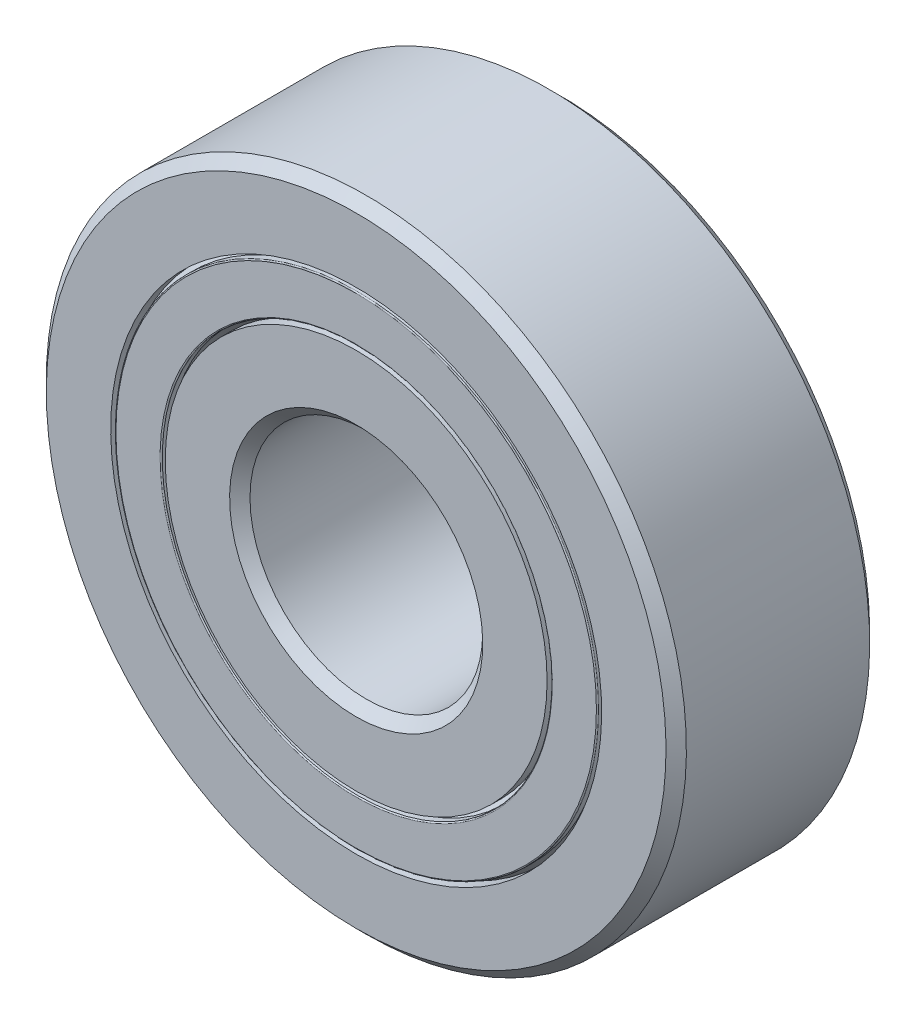
SolidWorks part; units mm, degrees
ref_plane "Front Plane" through (0, 0, 0) normal (0, 0, 1) x (1, 0, 0)
ref_plane "Top Plane" through (0, 0, 0) normal (0, 1, 0) x (1, 0, 0)
ref_plane "Right Plane" through (0, 0, 0) normal (1, 0, 0) x (0, 0, -1)
sketch "Sketch1" plane through (0, 0, 0) normal (0, 0, 1) x (1, 0, 0)
  line L0 (-11, 0) -> (11, 0) construction
  line L1 (-4, 0) -> (4, 0) construction
  circle A0 centre (0, 0) radius 4 construction
  circle A1 centre (0, 0) radius 11 construction
  point P3 (0, 0)
  point P6 (0, 0)
  point P7 (0, -4)
  point P11 (0, -11)
  point P12 (0, 4)
  point P13 (0, 11)
  dimension "OD" = 22
  dimension "ID" = 8
sketch "Sketch2" plane through (0, 0, 0) normal (1, 0, 0) x (0, 0, -1)
  line L0 (-3.5, 11) -> (3.5, 11) construction
  line L1 (0, 11) -> (0, -11) construction
  line L2 (3.15, 11) -> (-3.15, 11)
  line L3 (-3.15, 11) -> (-3.5, 10.65)
  line L4 (-3.5, 10.65) -> (-3.5, 8.4375)
  line L5 (-3.5, 8.4375) -> (-1.5556, 8.4375)
  line L6 (3.5, 8.4375) -> (1.5556, 8.4375)
  line L7 (3.5, 10.65) -> (3.5, 8.4375)
  line L8 (3.15, 11) -> (3.5, 10.65)
  line L9 (0, 11) -> (0, 7.5) construction
  line L10 (0, 7.5) -> (0, 4) construction
  line L11 (0, 11) -> (0, -11) construction
  line L12 (-3.5, 0) -> (3.5, 0) construction
  line L13 (3.5, 4) -> (-3.5, 4) construction
  line L14 (0, 9.3162) -> (0, 5.6838) construction
  line L15 (-3.5, -4) -> (3.5, -4) construction
  line L16 (-3.5, 4) -> (-3.5, -4) construction
  line L17 (3.5, 11) -> (3.5, -11) construction
  line L18 (-3.5, 8.4375) -> (-3.5, 8.3438) construction
  line L19 (-3.5, 8.3438) -> (-3.5, 8.25) construction
  line L20 (-3.5, 8.25) -> (-3.5, 8.1562) construction
  line L21 (-3.5, 8.1562) -> (-3.5, 8.0625) construction
  line L22 (-3.5, 8.0625) -> (-3.5, 7.9688) construction
  line L24 (-2.5278, 8.4375) -> (-2.5278, 7.5) construction
  arc A0 (-1.5556, 8.4375) -> (1.5556, 8.4375) centre (0, 7.5) cw
  circle A1 centre (0, 7.5) radius 1.8162 construction
  point P14 (0, 4)
  point P17 (0, 0)
  point P21 (0, 11)
  point P29 (0, 4)
  point P30 (0, -4)
  point P46 (-2.5278, 7.9688)
  dimension "Width" = 7
  dimension "D1" = 45
  dimension "D2" = 0.35
  dimension "D3" = 3.1111
  dimension "D4" = 0.9375
  dimension "For Shaft Diameter" = 8
  dimension "For Housing ID" = 22
sketch "Sketch3" plane through (0, 0, 0) normal (1, 0, 0) x (0, 0, -1)
  line L0 (3.15, 11) -> (3.5, 10.65) construction
  line L1 (3.5, 10.65) -> (3.5, 8.4375) construction
  line L2 (3.5, 8.4375) -> (1.5556, 8.4375) construction
  line L3 (-3.5, 8.4375) -> (-1.5556, 8.4375) construction
  line L4 (-3.5, 10.65) -> (-3.5, 8.4375) construction
  line L5 (-3.15, 11) -> (-3.5, 10.65) construction
  line L6 (3.15, 11) -> (-3.15, 11) construction
  line L7 (3.15, 11) -> (3.5, 10.65)
  line L8 (3.5, 10.65) -> (3.5, 8.4375)
  line L9 (3.5, 8.4375) -> (1.5556, 8.4375)
  line L10 (-3.5, 8.4375) -> (-1.5556, 8.4375)
  line L11 (-3.5, 10.65) -> (-3.5, 8.4375)
  line L12 (-3.15, 11) -> (-3.5, 10.65)
  line L13 (3.15, 11) -> (-3.15, 11)
  arc A0 (1.5556, 8.4375) -> (-1.5556, 8.4375) centre (0, 7.5) ccw construction
  arc A1 (1.5556, 8.4375) -> (-1.5556, 8.4375) centre (0, 7.5) ccw
revolve "Revolve1" add sketch "Sketch3" angle 360 about L12
sketch "Sketch4" plane through (0, 0, 0) normal (1, 0, 0) x (0, 0, -1)
  line L0 (0, 11) -> (0, -11) construction
  line L1 (0, 11) -> (0, -11) construction
  line L2 (-3.15, 4) -> (-3.5, 4.35)
  line L3 (-3.5, 4.35) -> (-3.5, 6.5625)
  line L5 (-3.5, 6.5625) -> (-1.5556, 6.5625)
  line L6 (-3.15, 4) -> (3.15, 4)
  line L8 (3.15, 4) -> (3.5, 4.35)
  line L10 (3.5, 4.35) -> (3.5, 6.5625)
  line L11 (3.5, 6.5625) -> (1.5556, 6.5625)
  line L12 (-3.5, 10.65) -> (-3.5, 8.4375) construction
  line L13 (3.15, 11) -> (3.5, 10.65) construction
  line L15 (3.5, -10.65) -> (3.5, 10.65) construction
  line L16 (3.15, 11) -> (3.15, -11) construction
  arc A1 (1.5556, 6.5625) -> (-1.5556, 6.5625) centre (0, 7.5) cw
  circle A2 centre (0, 7.5) radius 1.8162 construction
  point P1 (0, 4)
revolve "Revolve2" add sketch "Sketch4" angle 360 about L12
sketch "Sketch5" plane through (0, 0, 0) normal (1, 0, 0) x (0, 0, -1)
  line L0 (-1.8162, 7.5) -> (1.8162, 7.5)
  arc A2 (-1.8162, 7.5) -> (1.8162, 7.5) centre (0, 7.5) cw
  arc A3 (1.5556, 8.4375) -> (-1.5556, 8.4375) centre (0, 7.5) ccw construction
revolve "Revolve3" add sketch "Sketch5" angle 360 about L0
sketch "Sketch6" plane through (0, 0, 0) normal (1, 0, 0) x (0, 0, -1)
  line L0 (-3.5, 8.4375) -> (-3.5, 7.9688) construction
  line L1 (-3.5, 10.65) -> (-3.5, -10.65) construction
  line L2 (-3.5, 7.9688) -> (-3.5, 7.5) construction
  line L3 (-3.5, 7.5) -> (-3.5, 7.0312) construction
  line L4 (-3.5, 7.0312) -> (-3.5, 6.5625) construction
  line L5 (-3.5, 7.9688) -> (-3.2091, 7.9688) construction
  line L7 (-1.7547, 7.9687) -> (-1.7547, 7.0313) construction
  line L8 (-3.2091, 7.9688) -> (-2.9182, 7.9688) construction
  line L10 (0, 11) -> (0, -11) construction
  line L11 (0, 11) -> (0, -11) construction
  line L12 (-2.9182, 7.9688) -> (-2.6273, 7.9688) construction
  line L13 (-2.6273, 7.9688) -> (-2.3365, 7.9688) construction
  line L14 (-2.3365, 7.9688) -> (-2.0456, 7.9688) construction
  line L15 (-2.0456, 7.9688) -> (-1.7547, 7.9687) construction
  line L16 (-1.7547, 7.9687) -> (-2.0456, 7.9688)
  line L17 (-2.0456, 7.0313) -> (-2.3365, 7.0313) construction
  line L18 (-2.0456, 7.0313) -> (-1.7547, 7.0313)
  line L19 (-2.3365, 7.0313) -> (-2.3365, 7.9688) construction
  line L20 (-2.191, 7.9688) -> (-2.191, 7.0313) construction
  circle A0 centre (0, 7.5) radius 1.8162 construction
  circle A1 centre (0, 7.5) radius 1.8162 construction
  arc A2 (-2.0456, 7.9688) -> (-2.0456, 7.0313) centre (-1.3629, 7.5) ccw
  arc A3 (-1.7547, 7.9687) -> (-1.7547, 7.0313) centre (0, 7.5) ccw
  point P28 (-2.191, 7.5)
revolve "Revolve4" add sketch "Sketch6" angle 360 about L11
pattern_circular "CirPattern1" count 7 over 360 about axis through (0, 0, 0) along (0, 0, 1) of bodies 134 104
sketch "Sketch7" plane through (0, 0, 0) normal (0, 0, 1) x (1, 0, 0)
  line L0 (0, 6.5625) -> (0, 6.875) construction
  line L1 (0, 5.6838) -> (0, 9.3162) construction
  line L2 (0, 6.875) -> (0, 7.1875) construction
  line L3 (0, 7.1875) -> (0, 7.5) construction
  line L4 (0, 7.5) -> (0, 7.8125) construction
  line L5 (0, 7.8125) -> (0, 8.125) construction
  line L6 (0, 8.125) -> (0, 8.4375) construction
  line L7 (0, 10.65) -> (0, 8.4375) construction
  line L8 (0, 11) -> (0, -11) construction
  circle A0 centre (0, 0) radius 6.5625 construction
  circle A1 centre (0, 0) radius 7.5
  circle A2 centre (0, 0) radius 7.9688
  point P19 (0, 7.9688)
extrude "Boss-Extrude1" add sketch "Sketch7" along normal mid plane 1.1667 separate body
sketch "Sketch8" plane through (0, 0, 0) normal (1, 0, 0) x (0, 0, -1)
  line L0 (-3.5, 8.3438) -> (-3.5, 8.25) construction
  line L1 (-3.5, 8.2969) -> (-3.2407, 8.2969)
  line L2 (-3.5, 8.2969) -> (-3.5, 6.7031)
  line L3 (-3.5, 6.7031) -> (-3.2407, 6.7031)
  line L4 (-3.1111, 8.2969) -> (-3.1111, 6.7031)
  line L5 (0, 11) -> (0, 7.5) construction
  line L10 (-3.2407, 8.2969) -> (-3.1111, 8.4375)
  line L11 (-3.5, 8.4375) -> (-1.5556, 8.4375) construction
  line L12 (-3.1111, 8.4375) -> (-3.1111, 8.2969)
  line L13 (-3.2407, 6.7031) -> (-3.1111, 6.5625)
  line L14 (-3.1111, 6.5625) -> (-3.1111, 6.7031)
  line L15 (-3.5, 8.4375) -> (-3.3704, 8.4375) construction
  line L16 (3.5, 8.2969) -> (3.5, 6.7031)
  line L17 (3.5, 6.7031) -> (3.2407, 6.7031)
  line L18 (3.2407, 6.7031) -> (3.1111, 6.5625)
  line L19 (3.1111, 6.5625) -> (3.1111, 6.7031)
  line L20 (3.1111, 8.2969) -> (3.1111, 6.7031)
  line L21 (3.1111, 8.4375) -> (3.1111, 8.2969)
  line L22 (3.2407, 8.2969) -> (3.1111, 8.4375)
  line L23 (3.5, 8.2969) -> (3.2407, 8.2969)
  line L24 (-3.3704, 8.4375) -> (-3.2407, 8.4375) construction
  line L25 (-3.2407, 8.4375) -> (-3.1111, 8.4375) construction
  line L27 (-3.5, 6.5625) -> (-1.5556, 6.5625) construction
  point P23 (-3.5, 8.2969)
  dimension "D1" = 0.3889
revolve "Revolve5" add sketch "Sketch8" angle 360 about L12
fillet "Fillet1" radius 0.0389 2 edges at (0, -8.2969, 3.5) (0, -6.7031, 3.5)
fillet "Fillet2" radius 0.0389 2 edges at (0, -6.7031, -3.5) (0, -8.2969, -3.5)
equation "\"D2@Sketch2\" = \"Width@Sketch2\" * .05"
equation "\"D3@Sketch2\" = \"Width@Sketch2\" / 2.25"
equation "\"D4@Sketch2\"=( \"OD@Sketch1\" - \"Width@Sketch2\" )  *.5*.125"
equation "\"D1@Boss-Extrude1\" = \"Width@Sketch2\" / 6"
equation "\"D1@Sketch8\"=(\"Width@Sketch2\"-\"D3@Sketch2\")*.5*.2"
equation "\"D1@Fillet1\"=\"d1@sketch8\"*.1"
equation "\"D1@Fillet2\"=\"d1@fillet1\""
